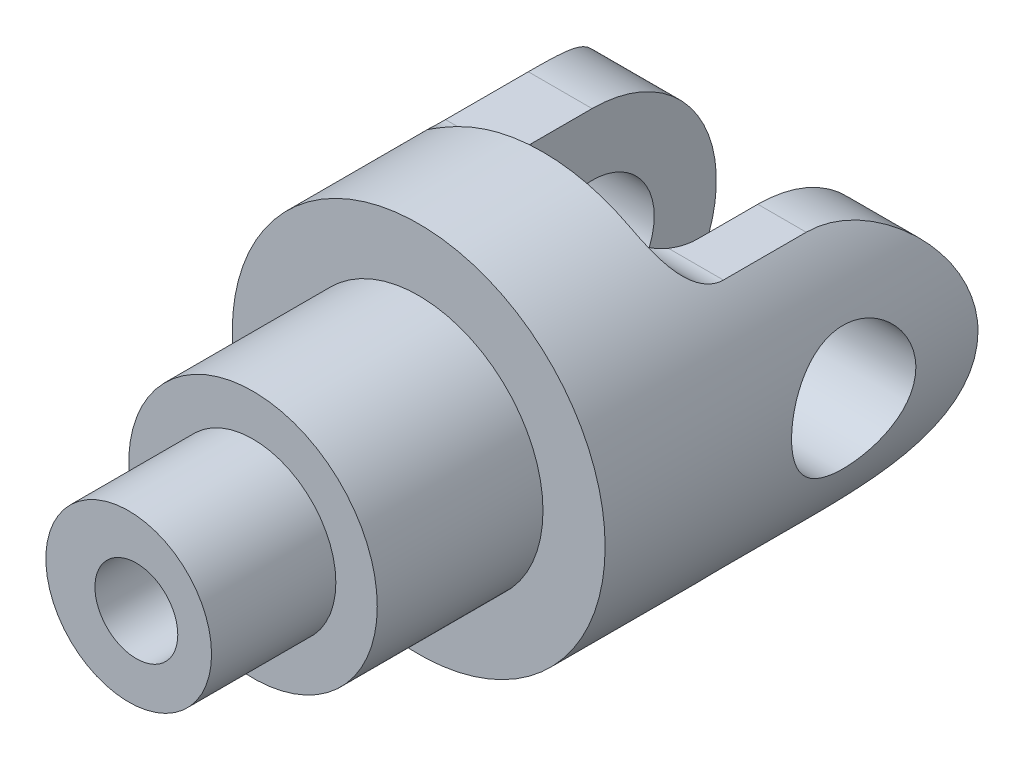
SolidWorks part; units mm, degrees
ref_plane "Front Plane" through (0, 0, 0) normal (0, 0, 1) x (1, 0, 0)
ref_plane "Top Plane" through (0, 0, 0) normal (0, 1, 0) x (1, 0, 0)
ref_plane "Right Plane" through (0, 0, 0) normal (1, 0, 0) x (0, 0, -1)
sketch "Sketch1" plane through (0, 0, 0) normal (0, 1, 0) x (1, 0, 0)
  line L0 (0, -35.9857) -> (0, 59.5012) construction
  line L1 (-1.8469, -35.9857) -> (-1.8469, 124.0143)
  line L3 (-46.8469, 124.0143) -> (-46.8469, 34.0143)
  line L4 (-46.8469, 34.0143) -> (-31.8469, 34.0143)
  line L7 (-31.8469, 34.0143) -> (-31.8469, -5.9857)
  line L8 (-31.8469, -5.9857) -> (-21.8469, -5.9857)
  line L11 (-21.8469, -5.9857) -> (-21.8469, -35.9857)
  line L12 (-21.8469, -35.9857) -> (-1.8469, -35.9857)
  line L14 (0, -35.9857) -> (-175.4679, -35.9857) construction
  line L15 (-46.8469, 124.0143) -> (-1.8469, 124.0143)
  dimension "D1" = 30
  dimension "D2" = 40
  dimension "D5" = 20
  dimension "D6" = 90
revolve "Revolve1" add sketch "Sketch1" angle 360 about L1
sketch "Sketch2" plane through (0, 0, 35.9857) normal (0, 0, 1) x (1, 0, 0)
  circle A0 centre (0, 0) radius 10
  dimension "D1" = 20
extrude "Cut-Extrude1" cut sketch "Sketch2" against normal blind 216
ref_plane "Plane1" through (0, 0, 0) normal (1, 0, 0) x (0, 0, -1)
sketch "Sketch4" plane through (0, 0, 0) normal (1, 0, 0) x (0, 0, -1)
  line L1 (34.0143, 45) -> (34.0143, -45) construction
  line L2 (64.0143, 45) -> (64.0143, 40)
  line L3 (124.0143, 45) -> (34.0143, 45) construction
  line L5 (94.0143, 30) -> (74.0143, 30)
  line L6 (0, 0) -> (31.4511, 0) construction
  line L7 (64.0143, -45) -> (64.0143, -40)
  line L8 (94.0143, -30) -> (74.0143, -30)
  line L9 (64.0143, 45) -> (124.0143, 45)
  line L10 (124.0143, 45) -> (124.0143, -45)
  line L11 (124.0143, -45) -> (64.0143, -45)
  circle A0 centre (94.0143, 0) radius 15
  arc A1 (94.0143, -30) -> (94.0143, 30) centre (94.0143, 0) ccw
  arc A2 (74.0143, 30) -> (64.0143, 40) centre (74.0143, 40) cw
  arc A3 (74.0143, -30) -> (64.0143, -40) centre (74.0143, -40) ccw
  dimension "D2" = 60
  dimension "D3" = 30
  dimension "D5" = 10
  dimension "D1" = 60
extrude "Cut-Extrude2" cut sketch "Sketch4" against normal mid plane 216 contours A2 L5 A1 L10 L9 L2 | L8 A3 L7 L11 L10 A1
ref_plane "Plane2" through (0, -30, 0) normal (0, -1, 0) x (-1, 0, 0)
sketch "Sketch5" plane through (0, -30, 0) normal (0, -1, 0) x (-1, 0, 0)
  line L1 (-20, 129.3672) -> (20, 129.3672)
  line L2 (-20, 129.3672) -> (-20, 79.3672)
  line L3 (-10, 69.3672) -> (10, 69.3672)
  line L4 (20, 129.3672) -> (20, 79.3672)
  arc A0 (10, 69.3672) -> (20, 79.3672) centre (10, 79.3672) ccw
  arc A1 (-20, 79.3672) -> (-10, 69.3672) centre (-10, 79.3672) ccw
  point P7 (0, 69.3672)
  point P12 (-20, 69.3672)
  dimension "D3" = 10
  dimension "D1" = 60
  dimension "D2" = 40
extrude "Cut-Extrude3" cut sketch "Sketch5" against normal mid plane 216
ref_plane "Plane3" through (0, 0, 0) normal (1, 0, 0) x (0, 0, -1)
sketch "Sketch7" plane through (0, 0, 0) normal (1, 0, 0) x (0, 0, -1)
  line L0 (34.0143, 45) -> (34.0143, -45) construction
  circle A0 centre (94.0143, 0) radius 15
  dimension "D1" = 30
  dimension "D2" = 60
extrude "Cut-Extrude4" cut sketch "Sketch7" against normal mid plane 216
